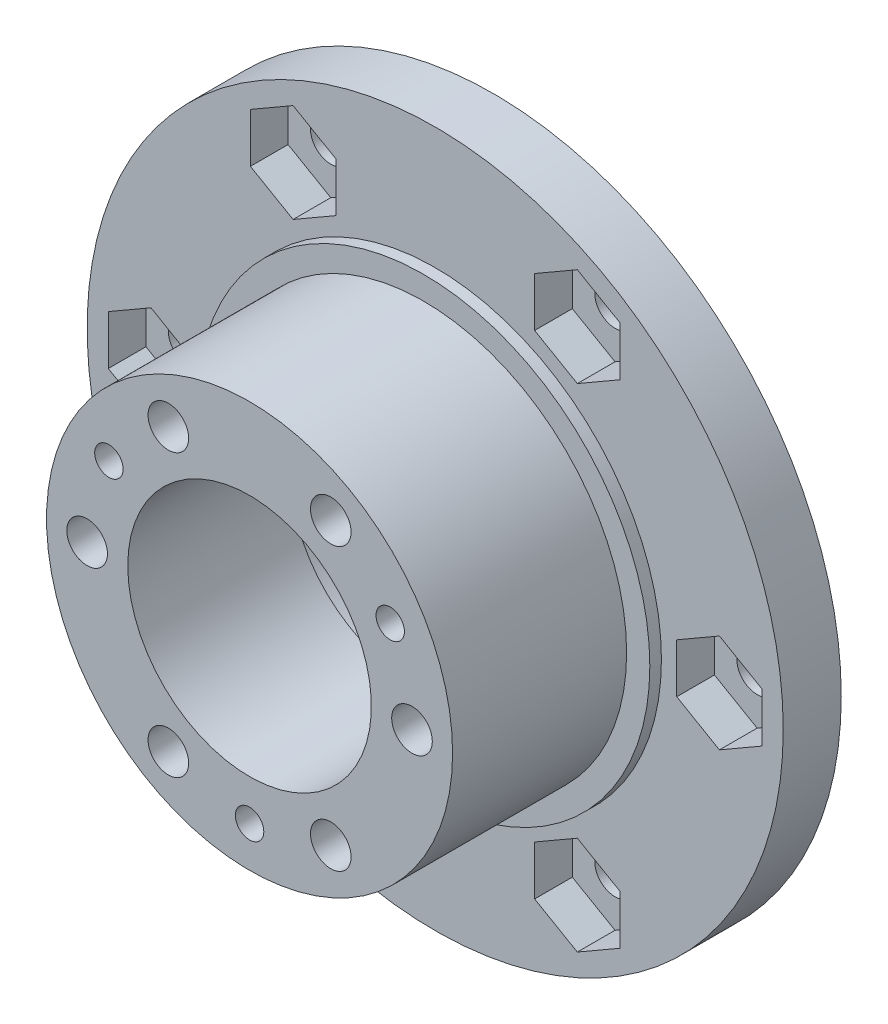
SolidWorks part; units mm, degrees
ref_plane "Front Plane" through (0, 0, 0) normal (0, 0, 1) x (1, 0, 0)
ref_plane "Top Plane" through (0, 0, 0) normal (0, 1, 0) x (1, 0, 0)
ref_plane "Right Plane" through (0, 0, 0) normal (1, 0, 0) x (0, 0, -1)
sketch "Sketch1" plane through (0, 0, 0) normal (0, 0, 1) x (1, 0, 0)
  circle A0 centre (0, 0) radius 30
  dimension "D1" = 60
extrude "Boss-Extrude1" add sketch "Sketch1" along normal blind 5
sketch "Sketch2" plane through (0, 0, 5) normal (0, 0, 1) x (1, 0, 0)
  circle A0 centre (0, 0) radius 19.5
  dimension "D1" = 39
extrude "Boss-Extrude2" add sketch "Sketch2" along normal blind 1
sketch "Sketch3" plane through (0, 0, 6) normal (0, 0, 1) x (1, 0, 0)
  circle A0 centre (0, 0) radius 17.5
  dimension "D1" = 35
extrude "Boss-Extrude3" add sketch "Sketch3" along normal blind 15
sketch "Sketch4" plane through (0, 0, 0) normal (0, 0, -1) x (-1, 0, 0)
  circle A0 centre (0, 0) radius 12.025
  dimension "D1" = 24.05
extrude "Cut-Extrude1" cut sketch "Sketch4" against normal blind 7 contours A0
sketch "Sketch5" plane through (0, 0, 7) normal (0, 0, -1) x (-1, 0, 0)
  circle A0 centre (0, 0) radius 10.5
  dimension "D1" = 21
extrude "Cut-Extrude2" cut sketch "Sketch5" against normal through all
sketch "Sketch6" plane through (0, 0, 5) normal (0, 0, 1) x (1, 0, 0)
  line L0 (0, 0) -> (33.6942, 0) construction
  circle A0 centre (0, 0) radius 24.5 construction
  circle A1 centre (24.5, 0) radius 1.75
  circle A2 centre (12.25, -21.2176) radius 1.75
  circle A3 centre (-12.25, -21.2176) radius 1.75
  circle A4 centre (-24.5, 0) radius 1.75
  circle A5 centre (-12.25, 21.2176) radius 1.75
  circle A6 centre (12.25, 21.2176) radius 1.75
  point P19 (0, 0)
  dimension "D1" = 49
  dimension "D2" = 3.5
  dimension "D3" = 6
extrude "Cut-Extrude3" cut sketch "Sketch6" against normal through all
sketch "Sketch7" plane through (0, 0, 21) normal (0, 0, 1) x (1, 0, 0)
  line L0 (0, 0) -> (34.5762, 0) construction
  circle A0 centre (0, 0) radius 14 construction
  circle A3 centre (14, 0) radius 1.75
  circle A5 centre (7, -12.1244) radius 1.75
  circle A6 centre (-7, -12.1244) radius 1.75
  circle A7 centre (-14, 0) radius 1.75
  circle A8 centre (-7, 12.1244) radius 1.75
  circle A9 centre (7, 12.1244) radius 1.75
  point P20 (0, 0)
  dimension "D1" = 28
  dimension "D2" = 3.5
  dimension "D3" = 6
extrude "Cut-Extrude4" cut sketch "Sketch7" against normal blind 10
sketch "Sketch8" plane through (0, 0, 21) normal (0, 0, 1) x (1, 0, 0)
  line L0 (0, 0) -> (28.2135, 16.2891) construction
  circle A0 centre (0, 0) radius 14 construction
  circle A1 centre (12.1244, 7) radius 1.225
  circle A2 centre (0, -14) radius 1.225
  circle A3 centre (-12.1244, 7) radius 1.225
  point P4 (12.1244, 7)
  point P15 (0, 0)
  dimension "D1" = 2.45
  dimension "D2" = 3
extrude "Cut-Extrude5" cut sketch "Sketch8" against normal blind 12
sketch "Sketch9" plane through (0, 0, 5) normal (0, 0, 1) x (1, 0, 0)
  line L0 (12.25, -16.9676) -> (8.5694, -19.0926)
  line L1 (24.5, 4.25) -> (20.8194, 2.125)
  line L2 (20.8194, 2.125) -> (20.8194, -2.125)
  line L3 (20.8194, -2.125) -> (24.5, -4.25)
  line L4 (24.5, -4.25) -> (28.1806, -2.125)
  line L5 (28.1806, -2.125) -> (28.1806, 2.125)
  line L6 (28.1806, 2.125) -> (24.5, 4.25)
  line L7 (15.9306, -19.0926) -> (12.25, -16.9676)
  line L8 (15.9306, -23.3426) -> (15.9306, -19.0926)
  line L9 (12.25, -25.4676) -> (15.9306, -23.3426)
  line L10 (8.5694, -23.3426) -> (12.25, -25.4676)
  line L11 (8.5694, -19.0926) -> (8.5694, -23.3426)
  line L12 (-8.5694, -19.0926) -> (-12.25, -16.9676)
  line L13 (-8.5694, -23.3426) -> (-8.5694, -19.0926)
  line L14 (-12.25, -25.4676) -> (-8.5694, -23.3426)
  line L15 (-15.9306, -23.3426) -> (-12.25, -25.4676)
  line L16 (-15.9306, -19.0926) -> (-15.9306, -23.3426)
  line L17 (-12.25, -16.9676) -> (-15.9306, -19.0926)
  line L18 (-20.8194, -2.125) -> (-20.8194, 2.125)
  line L19 (-24.5, -4.25) -> (-20.8194, -2.125)
  line L20 (-28.1806, -2.125) -> (-24.5, -4.25)
  line L21 (-28.1806, 2.125) -> (-28.1806, -2.125)
  line L22 (-24.5, 4.25) -> (-28.1806, 2.125)
  line L23 (-20.8194, 2.125) -> (-24.5, 4.25)
  line L24 (-12.25, 16.9676) -> (-8.5694, 19.0926)
  line L25 (-15.9306, 19.0926) -> (-12.25, 16.9676)
  line L26 (-15.9306, 23.3426) -> (-15.9306, 19.0926)
  line L27 (-12.25, 25.4676) -> (-15.9306, 23.3426)
  line L28 (-8.5694, 23.3426) -> (-12.25, 25.4676)
  line L29 (-8.5694, 19.0926) -> (-8.5694, 23.3426)
  line L30 (8.5694, 19.0926) -> (12.25, 16.9676)
  line L31 (8.5694, 23.3426) -> (8.5694, 19.0926)
  line L32 (12.25, 25.4676) -> (8.5694, 23.3426)
  line L33 (15.9306, 23.3426) -> (12.25, 25.4676)
  line L34 (15.9306, 19.0926) -> (15.9306, 23.3426)
  line L35 (12.25, 16.9676) -> (15.9306, 19.0926)
  circle A0 centre (24.5, 0) radius 3.6806 construction
  point P42 (0, 0)
  dimension "D1" = 4.25
  dimension "D2" = 6
extrude "Cut-Extrude6" cut sketch "Sketch9" against normal blind 3.25
